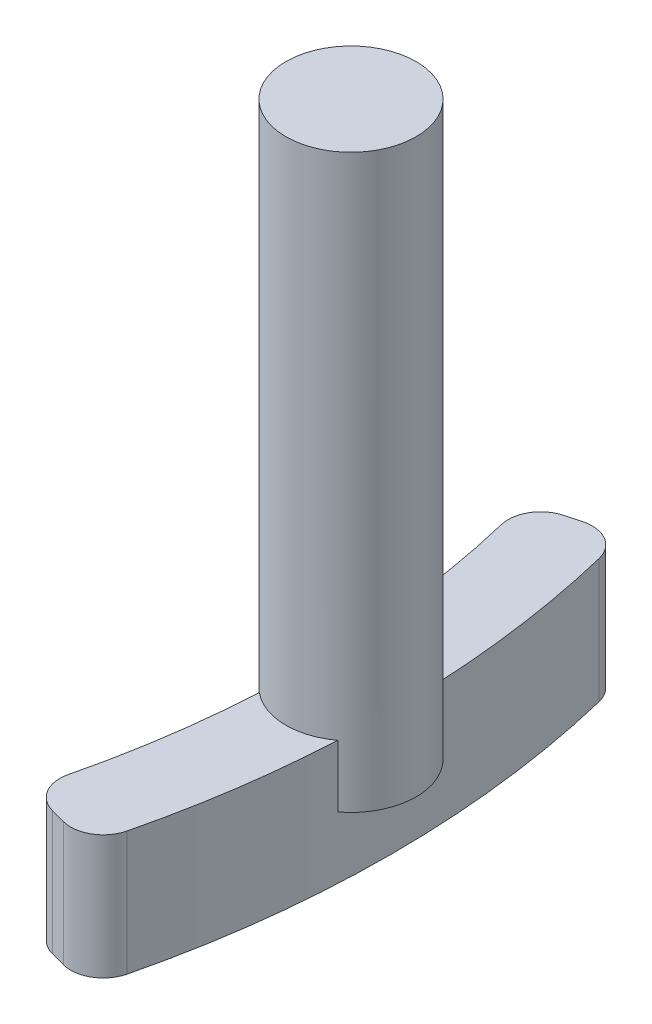
SolidWorks part; units mm, degrees
material "ABS"
ref_plane "Front Plane" through (0, 0, 0) normal (0, 0, 1) x (1, 0, 0)
ref_plane "Top Plane" through (0, 0, 0) normal (0, 1, 0) x (1, 0, 0)
ref_plane "Right Plane" through (0, 0, 0) normal (1, 0, 0) x (0, 0, -1)
sketch "Эскиз1" plane through (0, 0, 0) normal (0, 1, 0) x (1, 0, 0)
  line L8 (-0.953, -8.2461) -> (-0.4699, -8.3755)
  line L9 (-0.953, 8.2461) -> (-0.4699, 8.3755)
  arc A24 (0.8223, -7.6087) -> (-0.4699, -8.3755) centre (-0.1981, -7.3613) cw
  arc A25 (0.8223, -7.6087) -> (0.8223, 7.6087) centre (-30.5687, 0) ccw
  arc A26 (-0.4699, 8.3755) -> (0.8223, 7.6087) centre (-0.1981, 7.3613) cw
  arc A27 (-0.953, 8.2461) -> (-1.7018, 6.9849) centre (-0.6813, 7.2319) ccw
  arc A28 (-1.7018, -6.9849) -> (-1.7018, 6.9849) centre (-30.5687, 0) ccw
  arc A29 (-0.953, -8.2461) -> (-1.7018, -6.9849) centre (-0.6813, -7.2319) cw
  point P13 (0.3409, 8.2822)
  point P30 (0.3409, 8.2822)
  point P31 (0.3409, -8.2822)
extrude "Бобышка-Вытянуть1" add sketch "Эскиз1" along normal blind 4
ref_plane "Плоскость1" through (0, 2, 0) normal (0, 1, 0) x (1, 0, 0)
sketch "Эскиз2" plane through (0, 2, 0) normal (0, 1, 0) x (1, 0, 0)
  circle A2 centre (0.4313, 0) radius 2.1
  dimension "D1" = 4.2
extrude "Бобышка-Вытянуть2" add sketch "Эскиз2" along normal blind 18.44
